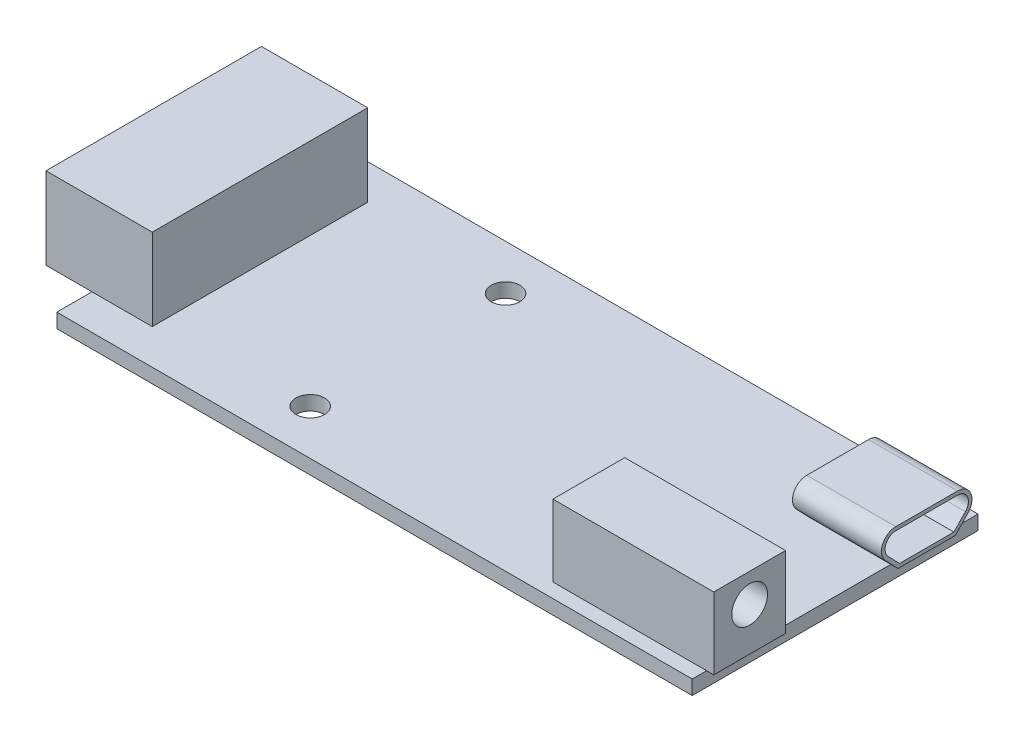
SolidWorks part; units mm, degrees
ref_plane "Front Plane" through (0, 0, 0) normal (0, 0, 1) x (1, 0, 0)
ref_plane "Top Plane" through (0, 0, 0) normal (0, 1, 0) x (1, 0, 0)
ref_plane "Right Plane" through (0, 0, 0) normal (1, 0, 0) x (0, 0, -1)
sketch "Sketch1" plane through (0, 0, 0) normal (0, 1, 0) x (1, 0, 0)
  line L0 (-7.625, 6.8) -> (-7.625, -6.8) construction
  line L1 (22.125, -9.95) -> (-22.125, -9.95)
  line L2 (22.125, -9.95) -> (22.125, 9.95)
  line L3 (22.125, 9.95) -> (-22.125, 9.95)
  line L4 (-22.125, -9.95) -> (-22.125, 9.95)
  line L5 (22.125, -9.95) -> (-22.125, 9.95) construction
  line L6 (22.125, 9.95) -> (-22.125, -9.95) construction
  circle A0 centre (-7.625, 6.8) radius 1
  circle A1 centre (-7.625, -6.8) radius 1
  point P0 (0, 0)
  point P8 (-7.625, 0)
  dimension "D5" = 2
  dimension "D1" = 19.9
  dimension "D2" = 44.25
  dimension "D3" = 14.5
  dimension "D4" = 13.6
extrude "Boss-Extrude1" add sketch "Sketch1" along normal blind 1
sketch "Sketch2" plane through (0, 1, 0) normal (0, 1, 0) x (1, 0, 0)
  line L0 (-22.125, 9.95) -> (-22.125, -9.95) construction
  line L1 (-25.325, 7.5) -> (-17.925, 7.5)
  line L2 (-25.325, 7.5) -> (-25.325, -7.5)
  line L3 (-25.325, -7.5) -> (-17.925, -7.5)
  line L4 (-17.925, 7.5) -> (-17.925, -7.5)
  point P4 (-17.925, 0)
  dimension "D1" = 15
  dimension "D2" = 7.4
  dimension "D3" = 3.2
extrude "Boss-Extrude2" add sketch "Sketch2" along normal blind 5.7
sketch "Sketch3" plane through (-25.325, 0, 0) normal (-1, 0, 0) x (0, 0, 1)
  line L4 (-7.5, 6.7) -> (-7.5, 1) construction
  line L5 (-6.8, 6) -> (6.8, 6)
  line L6 (-6.8, 6) -> (-6.8, 1.7)
  line L7 (-6.8, 1.7) -> (6.8, 1.7)
  line L8 (6.8, 6) -> (6.8, 1.7)
  line L9 (-7.5, 6.7) -> (7.5, 6.7) construction
  point P0 (0, 1.7)
  point P7 (-7.5, 3.85)
  point P9 (-6.8, 3.85)
  dimension "D1" = 0.7
  dimension "D2" = 0.7
extrude "Cut-Extrude1" cut sketch "Sketch3" against normal blind 6
sketch "Sketch4" plane through (0, 1, 0) normal (0, 1, 0) x (1, 0, 0)
  line L0 (-22.125, -9.95) -> (22.125, -9.95) construction
  line L1 (11.425, -3.95) -> (22.625, -3.95)
  line L2 (11.425, -3.95) -> (11.425, -8.95)
  line L3 (11.425, -8.95) -> (22.625, -8.95)
  line L4 (22.625, -3.95) -> (22.625, -8.95)
  line L5 (22.125, -9.95) -> (22.125, 9.95) construction
  dimension "D1" = 5
  dimension "D2" = 11.2
  dimension "D3" = 1
  dimension "D4" = 0.5
extrude "Boss-Extrude3" add sketch "Sketch4" along normal blind 5
sketch "Sketch5" plane through (22.625, 0, 0) normal (1, 0, 0) x (0, 0, -1)
  line L0 (-8.95, 6) -> (-3.95, 6) construction
  circle A0 centre (-6.45, 4) radius 1.25
  point P4 (-6.45, 6)
  dimension "D1" = 2
  dimension "D2" = 2.5
extrude "Cut-Extrude2" cut sketch "Sketch5" against normal blind 8
sketch "Sketch6" plane through (22.125, 0, 0) normal (1, 0, 0) x (0, 0, -1)
  line L0 (3.8792, 1) -> (7.8792, 1)
  line L1 (-3.95, 1) -> (9.95, 1) construction
  line L2 (7.8792, 1) -> (8.7512, 1.9069)
  line L3 (8.0303, 3.6) -> (3.728, 3.6)
  line L4 (3.0072, 1.9069) -> (3.8792, 1)
  line L5 (-7.5, 1) -> (7.5, 1) construction
  line L6 (3.9856, 1.25) -> (7.7727, 1.25)
  line L7 (7.7727, 1.25) -> (8.571, 2.0802)
  line L8 (8.0303, 3.35) -> (3.728, 3.35)
  line L9 (3.1874, 2.0802) -> (3.9856, 1.25)
  arc A0 (8.7512, 1.9069) -> (8.0303, 3.6) centre (8.0303, 2.6) ccw
  arc A1 (3.728, 3.6) -> (3.0072, 1.9069) centre (3.728, 2.6) ccw
  arc A2 (8.571, 2.0802) -> (8.0303, 3.35) centre (8.0303, 2.6) ccw
  arc A3 (3.728, 3.35) -> (3.1874, 2.0802) centre (3.728, 2.6) ccw
  point P7 (5.8792, 3.6)
  point P8 (5.8792, 1)
  point P14 (10.3792, 3.6)
  point P17 (1.3792, 3.6)
  dimension "D3" = 1
  dimension "D1" = 9
  dimension "D2" = 2.6
  dimension "D4" = 4
  dimension "D5" = 0.25
extrude "Boss-Extrude4" add sketch "Sketch6" against normal blind 5.7 and the other way blind 0.5
